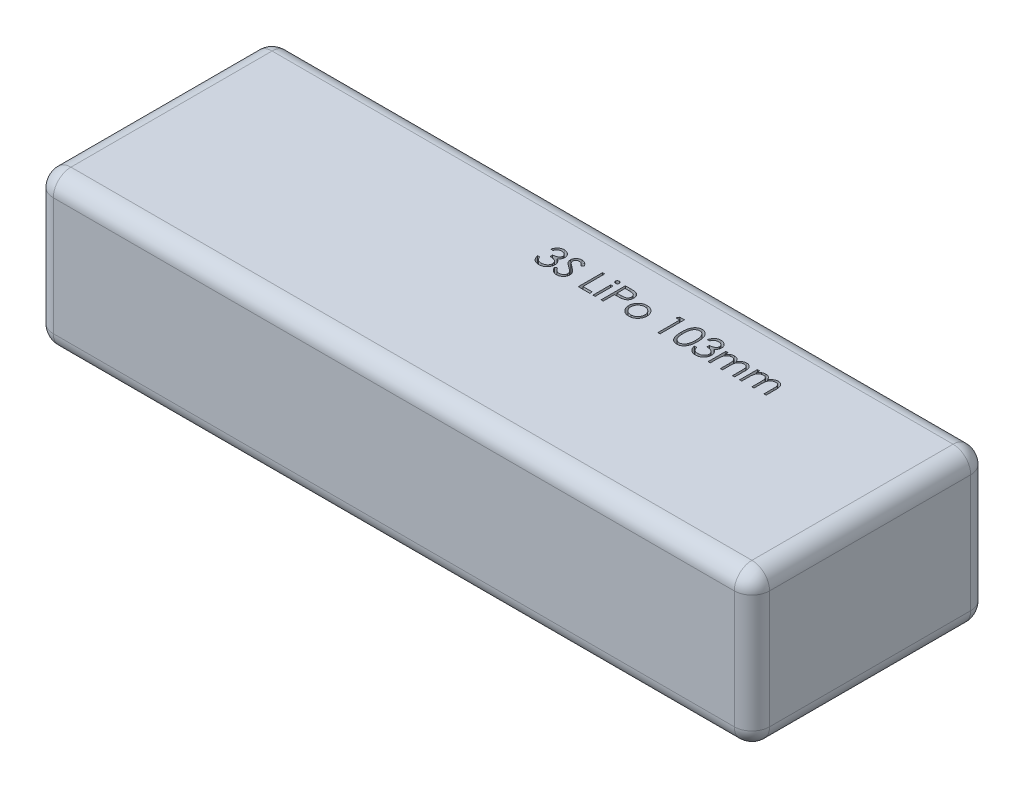
SolidWorks part; units mm, degrees
material "AA356.0-F"
ref_plane "Front Plane" through (0, 0, 0) normal (0, 0, 1) x (1, 0, 0)
ref_plane "Top Plane" through (0, 0, 0) normal (0, 1, 0) x (1, 0, 0)
ref_plane "Right Plane" through (0, 0, 0) normal (1, 0, 0) x (0, 0, -1)
sketch "Sketch1" plane through (0, 0, 0) normal (0, 1, 0) x (1, 0, 0)
  line L1 (0, 0) -> (103, 0)
  line L2 (0, 0) -> (0, 34)
  line L3 (0, 34) -> (103, 34)
  line L4 (103, 0) -> (103, 34)
  dimension "D1" = 103
  dimension "D2" = 34
extrude "Boss-Extrude1" add sketch "Sketch1" along normal blind 22
fillet "Fillet1" radius 2.54 4 edges at (51.5, 0, 0) (51.5, 0, -34) (51.5, 22, -34) (51.5, 22, 0)
fillet "Fillet2" radius 2.54 16 edges at (103, 21.2561, -0.7439) (103, 11, 0) (103, 0.7439, -0.7439) (103, 0.7439, -33.2561) (103, 11, -34) (103, 21.2561, -33.2561) (0, 21.2561, -33.2561) (0, 11, -34) (0, 0.7439, -33.2561) (0, 0.7439, -0.7439) (0, 11, 0) (0, 21.2561, -0.7439) (103, 0, -17) (103, 22, -17) (0, 0, -17) (0, 22, -17)
sketch "Sketch2" plane through (0, 22, 0) normal (0, 1, 0) x (1, 0, 0)
  line L0 (2.54, 31.46) -> (2.54, 2.54) construction
  line L1 (2.54, 2.54) -> (100.46, 2.54) construction
  text T0 "3S LiPo 103mm"
  dimension "D1" = 44.45
  dimension "D2" = 21.59
extrude "Cut-Extrude1" cut sketch "Sketch2" against normal blind 2.54
